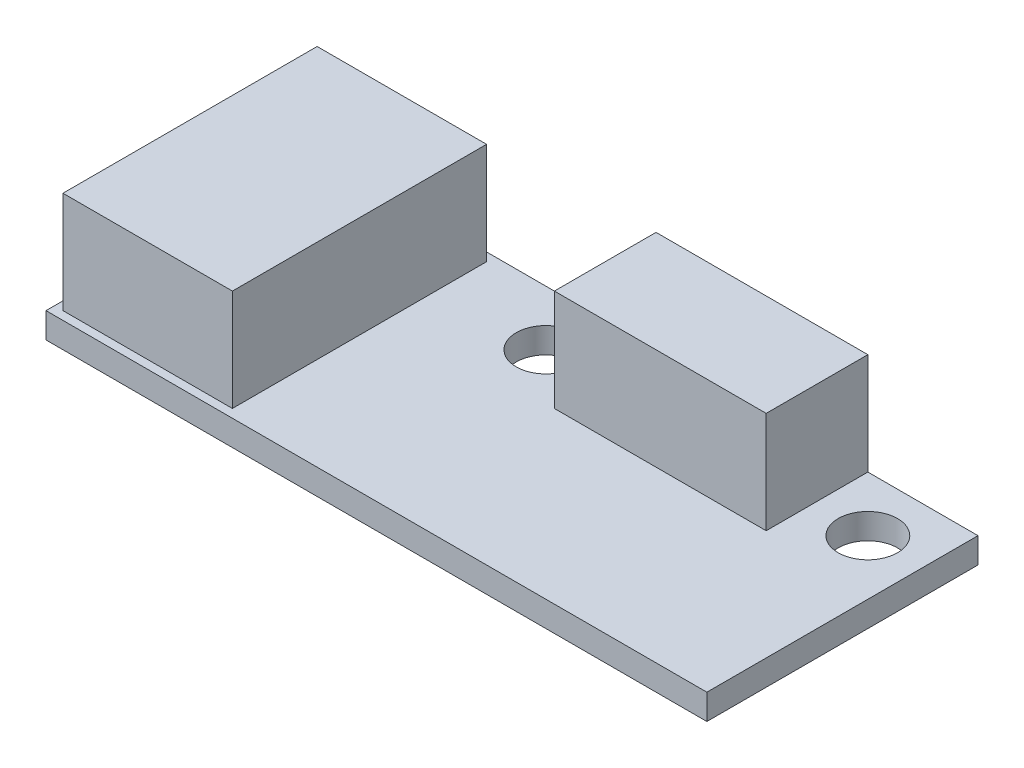
SolidWorks part; units mm, degrees
ref_plane "前视基准面" through (0, 0, 0) normal (0, 0, 1) x (1, 0, 0)
ref_plane "上视基准面" through (0, 0, 0) normal (0, 1, 0) x (1, 0, 0)
ref_plane "右视基准面" through (0, 0, 0) normal (1, 0, 0) x (0, 0, -1)
sketch "草图1" plane through (0, 0, 0) normal (0, 1, 0) x (1, 0, 0)
  line L1 (-19.5, -8) -> (19.5, -8)
  line L2 (-19.5, -8) -> (-19.5, 8)
  line L3 (-19.5, 8) -> (19.5, 8)
  line L4 (19.5, -8) -> (19.5, 8)
  line L5 (-19.5, -8) -> (19.5, 8) construction
  line L6 (-19.5, 8) -> (19.5, -8) construction
  point P0 (0, 0)
  dimension "D1" = 39
  dimension "D2" = 16
extrude "凸台-拉伸1" add sketch "草图1" along normal blind 1.5
sketch "草图2" plane through (0, 1.5, 0) normal (0, 1, 0) x (1, 0, 0)
  line L0 (19.5, 8) -> (-19.5, 8) construction
  line L1 (19.5, -8) -> (19.5, 8) construction
  circle A0 centre (16.25, 4.75) radius 1.75
  circle A1 centre (-2.75, 4.75) radius 1.75
  dimension "D1" = 3.5
  dimension "D2" = 3.25
  dimension "D3" = 3.25
  dimension "D4" = 19
  dimension "D5" = 3.5
  dimension "D6" = 3.25
extrude "切除-拉伸1" cut sketch "草图2" against normal blind 1.5
sketch "草图3" plane through (0, 1.5, 0) normal (0, 1, 0) x (1, 0, 0)
  line L0 (19.5, 8) -> (-19.5, 8) construction
  line L1 (13, 8) -> (0.5, 8)
  line L2 (13, 8) -> (13, 2)
  line L3 (13, 2) -> (0.5, 2)
  line L4 (0.5, 8) -> (0.5, 2)
  circle A0 centre (-2.75, 4.75) radius 1.75 construction
  dimension "D1" = 12.5
  dimension "D2" = 3.25
  dimension "D3" = 6
extrude "凸台-拉伸2" add sketch "草图3" along normal blind 6
sketch "草图4" plane through (0, 1.5, 0) normal (0, 1, 0) x (1, 0, 0)
  line L3 (-9, 7.5) -> (-9, -7.5)
  line L6 (-19, -7.5) -> (19.5, -7.5)
  line L7 (-19, 7.5) -> (-19, -7.5)
  line L8 (0.5, 7.5) -> (-19, 7.5)
  line L9 (-19, -7.5) -> (-9, -7.5)
  line L10 (-19, 7.5) -> (-19, -7.5)
  line L11 (-9, 7.5) -> (-19, 7.5)
  dimension "D2" = 10
  dimension "D1" = 0.5
extrude "凸台-拉伸3" add sketch "草图4" along normal blind 6
